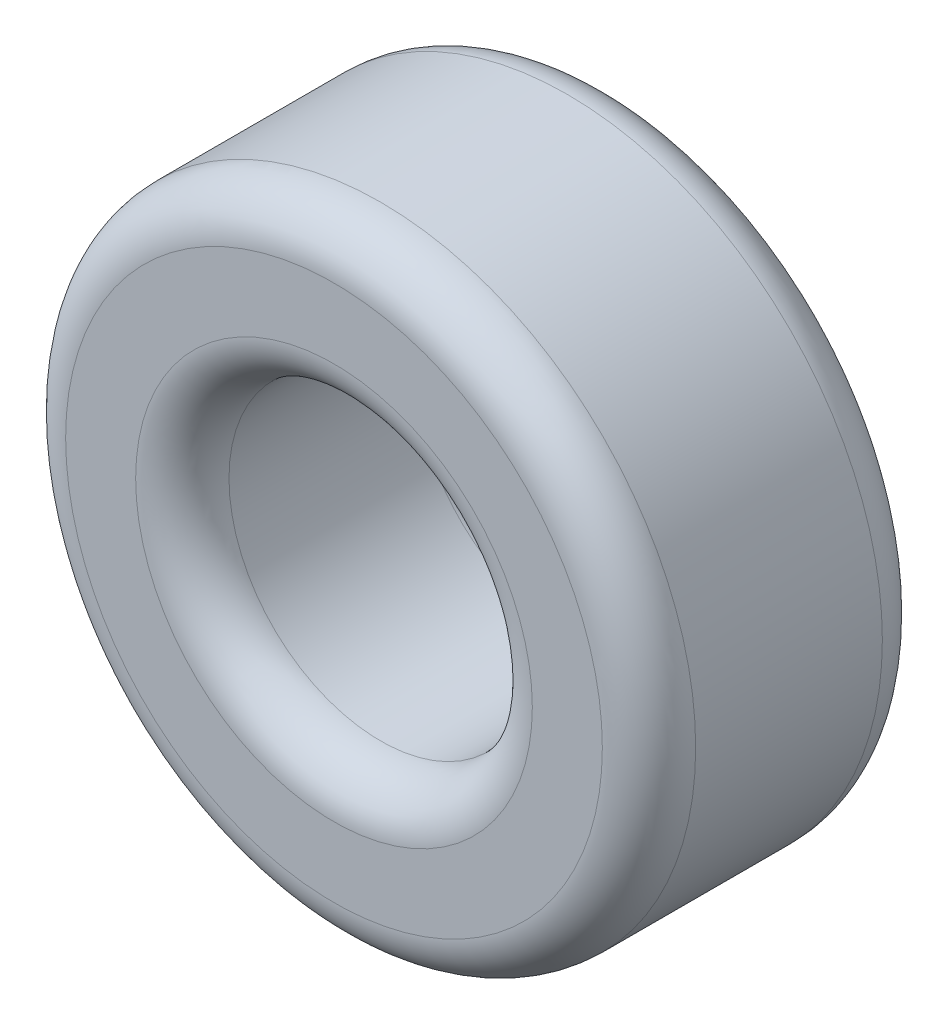
SolidWorks part; units mm, degrees
ref_plane "Спереди" through (0, 0, 0) normal (0, 0, 1) x (1, 0, 0)
ref_plane "Сверху" through (0, 0, 0) normal (0, 1, 0) x (1, 0, 0)
ref_plane "Справа" through (0, 0, 0) normal (1, 0, 0) x (0, 0, -1)
sketch "Эскиз1" plane through (0, 0, 0) normal (0, 0, 1) x (1, 0, 0)
  circle A0 centre (0, 0) radius 27
  circle A1 centre (0, 0) radius 13
  dimension "D1" = 54
  dimension "D2" = 26
extrude "Вытянуть1" add sketch "Эскиз1" along normal blind 24
fillet "Скругление1" radius 4
